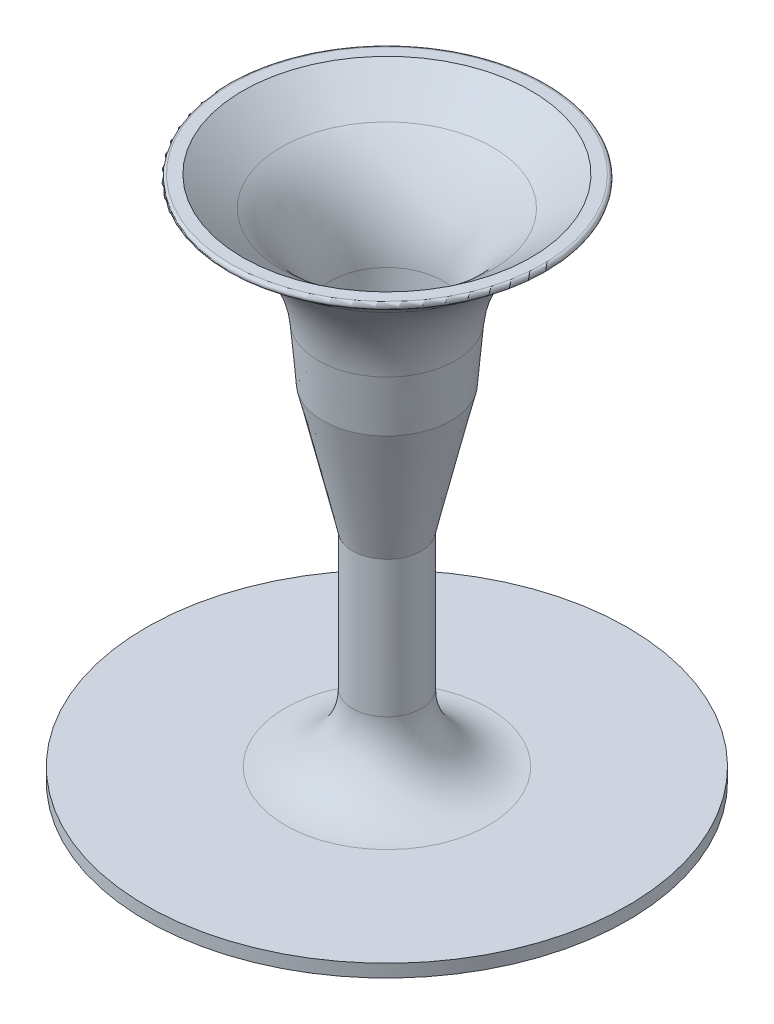
SolidWorks part; units mm, degrees
ref_plane "Front Plane" through (0, 0, 0) normal (0, 0, 1) x (1, 0, 0)
ref_plane "Top Plane" through (0, 0, 0) normal (0, 1, 0) x (1, 0, 0)
ref_plane "Right Plane" through (0, 0, 0) normal (1, 0, 0) x (0, 0, -1)
sketch "Sketch1" plane through (0, 0, 0) normal (0, 0, 1) x (1, 0, 0)
  line L0 (0, 74.3905) -> (0, -74.3905) construction
  line L1 (0, -50) -> (-3.35, -50)
  line L2 (-3.35, -50) -> (-3.35, -20)
  line L3 (-3.35, -20) -> (-8, 0)
  line L4 (-8, 0) -> (-8.7663, 9.1953)
  line L5 (-8, 0) -> (0, 0) construction
  line L6 (-9.5, 18) -> (0, 18) construction
  line L7 (-16.503, 23.3869) -> (-22.5, 28)
  line L8 (-22.5, 28) -> (0, 28) construction
  line L9 (0, -52) -> (-5.35, -52)
  line L10 (-5.35, -52) -> (-5.35, -20.2294)
  line L11 (-5.35, -20.2294) -> (-9.981, -0.3111)
  line L12 (-9.981, -0.3111) -> (-10.686, 8.1488)
  line L13 (-18.4227, 22.3403) -> (-23.7194, 26.4148)
  line L14 (-23.7194, 26.4148) -> (-25.7802, 28)
  line L15 (-25.7802, 28) -> (-22.5, 28)
  line L16 (0, -50) -> (0, -52)
  line L17 (-9.981, -0.3111) -> (-11.4197, 16.9534) construction
  line L18 (-11.4197, 16.9534) -> (-23.7194, 26.4148) construction
  line L19 (-8, 0) -> (-9.5, 18) construction
  line L20 (-9.5, 18) -> (-22.5, 28) construction
  arc A0 (-10.686, 8.1488) -> (-18.4227, 22.3403) centre (-30.6169, 6.4879) ccw
  arc A1 (-8.7663, 9.1953) -> (-16.503, 23.3869) centre (-28.6972, 7.5344) ccw
  point P4 (0, 0)
  point P20 (0, 0)
  dimension "D2" = 30
  dimension "D10" = 20
  dimension "D1" = 3.35
  dimension "D3" = 20
  dimension "D4" = 16
  dimension "D5" = 19
  dimension "D6" = 18
  dimension "D7" = 45
  dimension "D8" = 10
  dimension "D9" = 2
revolve "Revolve1" add sketch "Sketch1" angle 360 about L0
fillet "Fillet1" radius 0.5 1 edges at (0, 28, 25.7802)
sketch "Sketch2" plane through (0, -52, 0) normal (0, -1, 0) x (1, 0, 0)
  circle A0 centre (0, 0) radius 37.5547
extrude "Boss-Extrude1" add sketch "Sketch2" along normal blind 2
fillet "Fillet2" radius 10.5 1 edges at (0, -52, 5.35)
